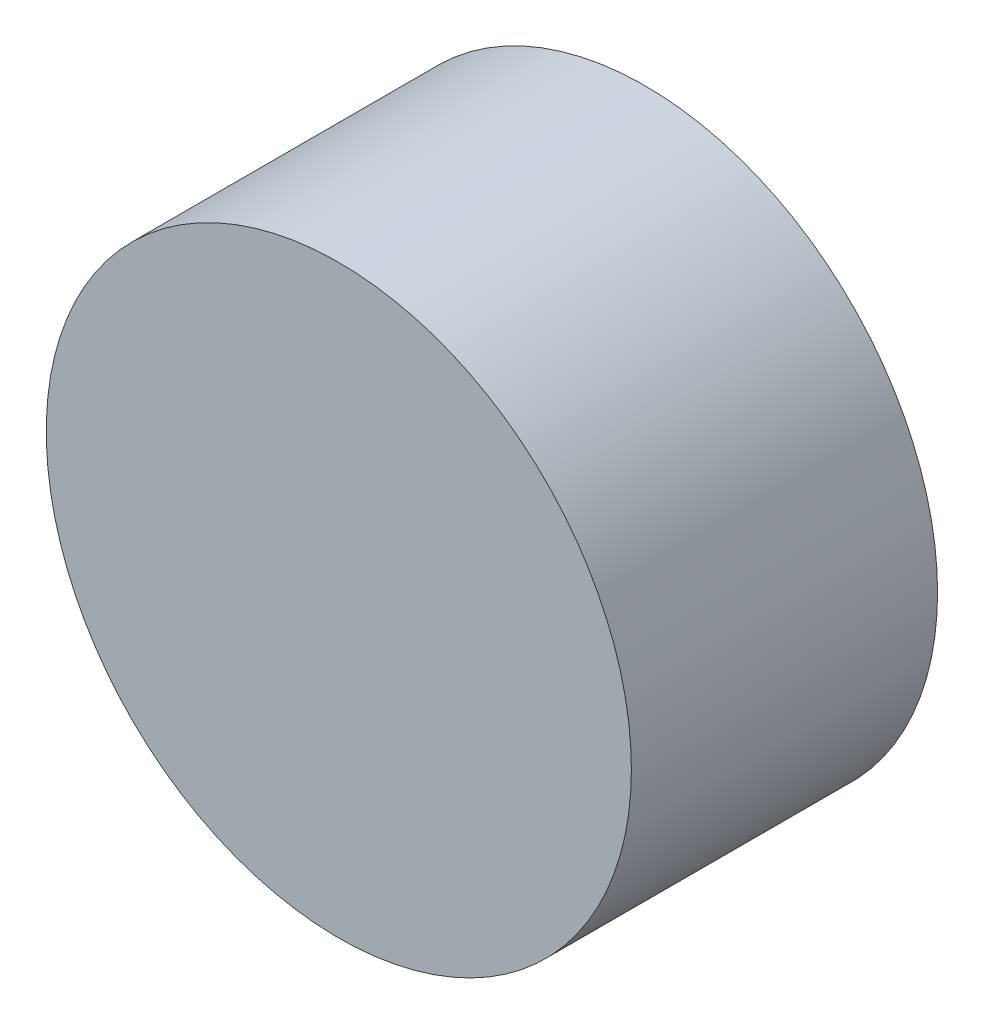
SolidWorks part; units mm, degrees
ref_plane "Front Plane" through (0, 0, 0) normal (0, 0, 1) x (1, 0, 0)
ref_plane "Top Plane" through (0, 0, 0) normal (0, 1, 0) x (1, 0, 0)
ref_plane "Right Plane" through (0, 0, 0) normal (1, 0, 0) x (0, 0, -1)
sketch "Sketch1" plane through (0, 0, 0) normal (0, 0, 1) x (1, 0, 0)
  circle A0 centre (0, 0) radius 27.5
  circle A1 centre (0, 0) radius 43
  dimension "D1" = 86
  dimension "D2" = 55
extrude "Boss-Extrude1" add sketch "Sketch1" along normal blind 40
sketch "Sketch2" plane through (0, 0, 40) normal (0, 0, 1) x (1, 0, 0)
  circle A5 centre (0, 0) radius 43 construction
  circle A6 centre (0, 0) radius 43
extrude "Boss-Extrude2" add sketch "Sketch2" along normal blind 5
sketch "Sketch3" plane through (0, 0, 40) normal (0, 0, -1) x (-1, 0, 0)
  line L1 (6.3509, 11) -> (-6.3509, 11)
  line L2 (-6.3509, 11) -> (-12.7017, 0)
  line L3 (-12.7017, 0) -> (-6.3509, -11)
  line L4 (-6.3509, -11) -> (6.3509, -11)
  line L5 (6.3509, -11) -> (12.7017, 0)
  line L6 (12.7017, 0) -> (6.3509, 11)
  line L7 (3.4641, 6) -> (-3.4641, 6)
  line L8 (-3.4641, 6) -> (-6.9282, 0)
  line L9 (-6.9282, 0) -> (-3.4641, -6)
  line L10 (-3.4641, -6) -> (3.4641, -6)
  line L11 (3.4641, -6) -> (6.9282, 0)
  line L12 (6.9282, 0) -> (3.4641, 6)
  circle A0 centre (0, 0) radius 11 construction
  circle A1 centre (0, 0) radius 6 construction
  dimension "D1" = 12
  dimension "D2" = 5
extrude "Boss-Extrude3" add sketch "Sketch3" along normal blind 10
